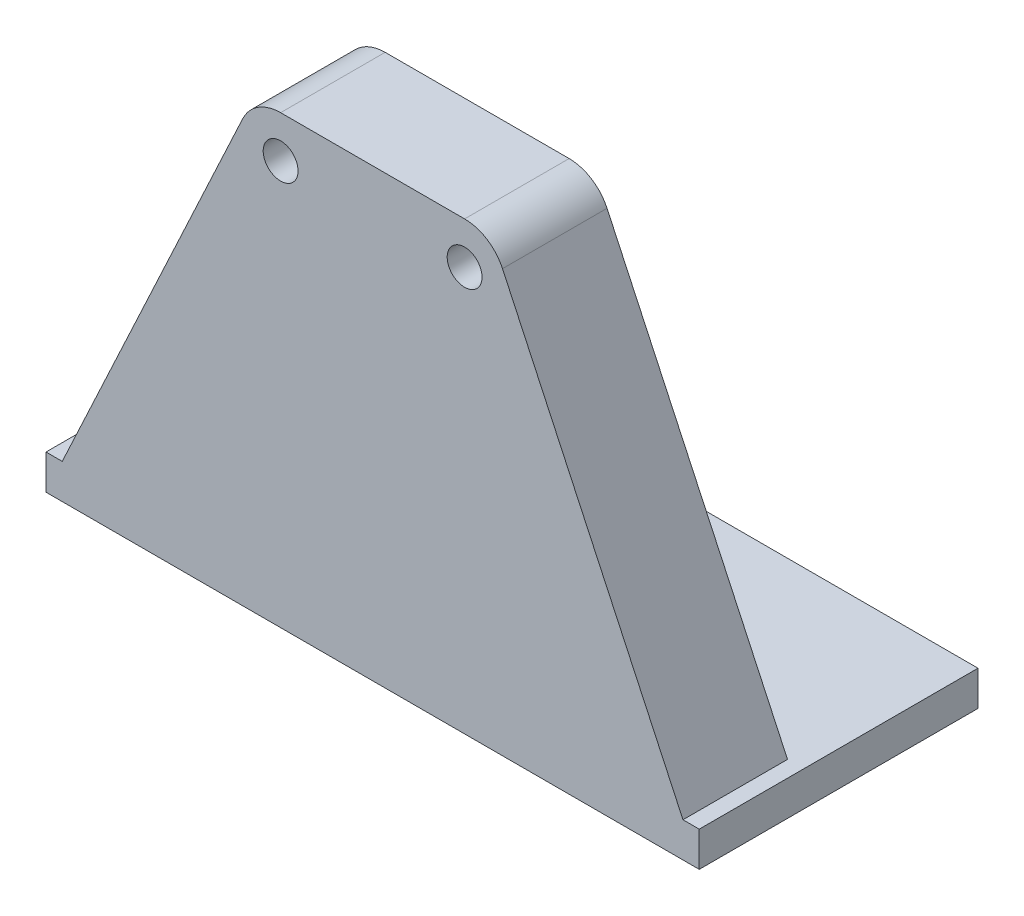
SolidWorks part; units mm, degrees
material "6061 Alloy"
ref_plane "Front" through (0, 0, 0) normal (0, 0, 1) x (1, 0, 0)
ref_plane "Top" through (0, 0, 0) normal (0, 1, 0) x (1, 0, 0)
ref_plane "Right" through (0, 0, 0) normal (1, 0, 0) x (0, 0, -1)
sketch "Sketch1" plane through (0, 0, 0) normal (0, 0, 1) x (1, 0, 0)
  line L0 (0, 0) -> (13.9549, 0) construction
  line L1 (0, 0) -> (17.9249, 38.4402)
  line L2 (21.378, 40.64) -> (38.142, 40.64)
  line L3 (41.595, 38.4402) -> (59.52, 0)
  line L4 (0, 0) -> (59.52, 0)
  circle A0 centre (21.378, 36.83) radius 1.5875
  circle A1 centre (38.142, 36.83) radius 1.5875
  arc A2 (17.9249, 38.4402) -> (21.378, 40.64) centre (21.378, 36.83) cw
  arc A3 (38.142, 40.64) -> (41.595, 38.4402) centre (38.142, 36.83) cw
  dimension "D1" = 16.764
  dimension "D2" = 3.175
  dimension "D4" = 65
  dimension "D6" = 3.81
  dimension "D3" = 36.83
  dimension "D5" = 65
extrude "Boss-Extrude1" add sketch "Sketch1" along normal blind 9.525
sketch "Sketch2" plane through (0, 0, 9.525) normal (0, 0, 1) x (1, 0, 0)
  line L1 (0, 0) -> (59.52, 0)
  line L2 (0, 0) -> (0, 3.175)
  line L3 (0, 3.175) -> (59.52, 3.175)
  line L4 (59.52, 0) -> (59.52, 3.175)
  dimension "D1" = 3.175
extrude "Boss-Extrude2" add sketch "Sketch2" against normal blind 25.4
